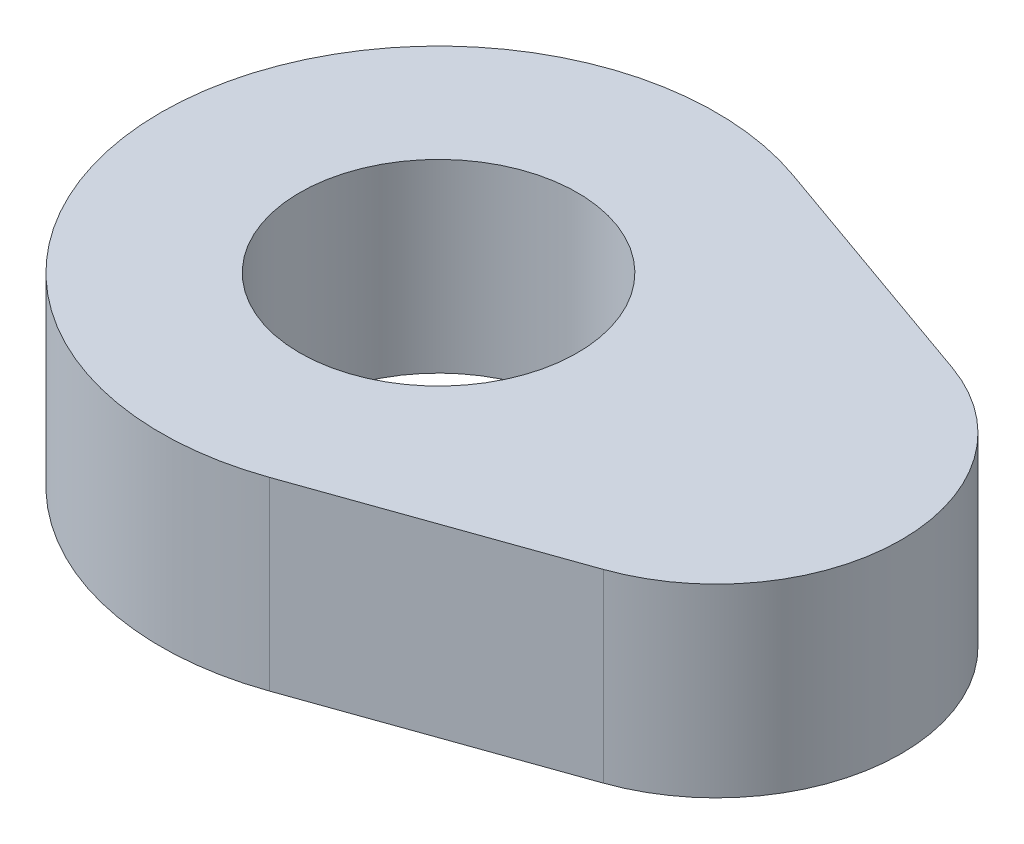
SolidWorks part; units mm, degrees
ref_plane "前视基准面" through (0, 0, 0) normal (0, 0, 1) x (1, 0, 0)
ref_plane "上视基准面" through (0, 0, 0) normal (0, 1, 0) x (1, 0, 0)
ref_plane "右视基准面" through (0, 0, 0) normal (1, 0, 0) x (0, 0, -1)
other "Configuration Table"
sketch "草图1" plane through (0, 0, 0) normal (0, 1, 0) x (1, 0, 0)
  line L0 (-0.7599, 9.9586) -> (12.5735, 5.2445)
  line L1 (-0.7599, -18.3257) -> (12.5735, -13.6117)
  line L2 (-5.7599, -4.1836) -> (9.2401, -4.1836) construction
  arc A0 (-0.7599, 9.9586) -> (-0.7599, -18.3257) centre (-5.7599, -4.1836) ccw
  arc A1 (12.5735, 5.2445) -> (12.5735, -13.6117) centre (9.2401, -4.1836) cw
  dimension "D2" = 10
  dimension "D3" = 15
  dimension "D1" = 15
extrude "凸台-拉伸1" add sketch "草图1" along normal blind 10
sketch "草图2" plane through (0, 10, 0) normal (0, 1, 0) x (1, 0, 0)
  circle A0 centre (-5.7599, -4.1836) radius 7.5 construction
  circle A1 centre (-5.7599, -4.1836) radius 7.5
extrude "切除-拉伸1" cut sketch "草图2" against normal blind 10
